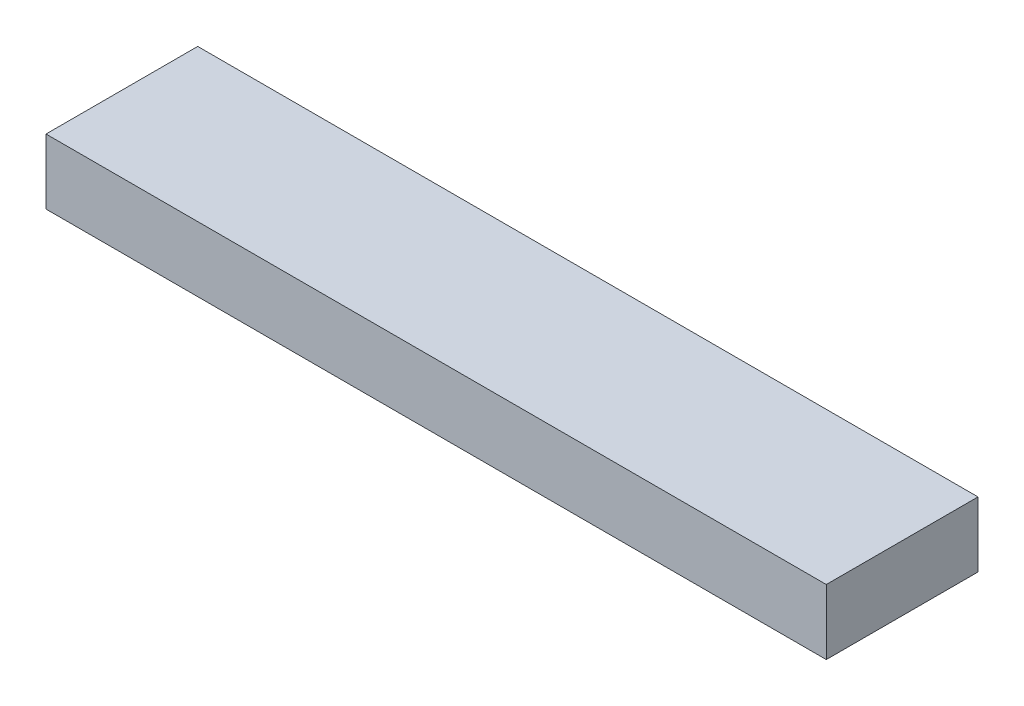
SolidWorks part; units mm, degrees
ref_plane "Front Plane" through (0, 0, 0) normal (0, 0, 1) x (1, 0, 0)
ref_plane "Top Plane" through (0, 0, 0) normal (0, 1, 0) x (1, 0, 0)
ref_plane "Right Plane" through (0, 0, 0) normal (1, 0, 0) x (0, 0, -1)
sketch "Sketch1" plane through (0, 0, 0) normal (0, 1, 0) x (1, 0, 0)
  line L1 (-56.46, 10.4673) -> (400.74, 10.4673)
  line L2 (-56.46, 10.4673) -> (-56.46, -78.4327)
  line L3 (-56.46, -78.4327) -> (400.74, -78.4327)
  line L4 (400.74, 10.4673) -> (400.74, -78.4327)
  dimension "D1" = 88.9
  dimension "D2" = 457.2
extrude "Boss-Extrude1" add sketch "Sketch1" along normal blind 38.1
sketch "Sketch2" plane through (0, 0, 0) normal (0, -1, 0) x (1, 0, 0)
  line L0 (400.74, 33.9827) -> (-56.46, 33.9827) construction
  line L1 (400.74, 78.4327) -> (400.74, -10.4673) construction
  line L2 (-56.46, -10.4673) -> (-56.46, 78.4327) construction
